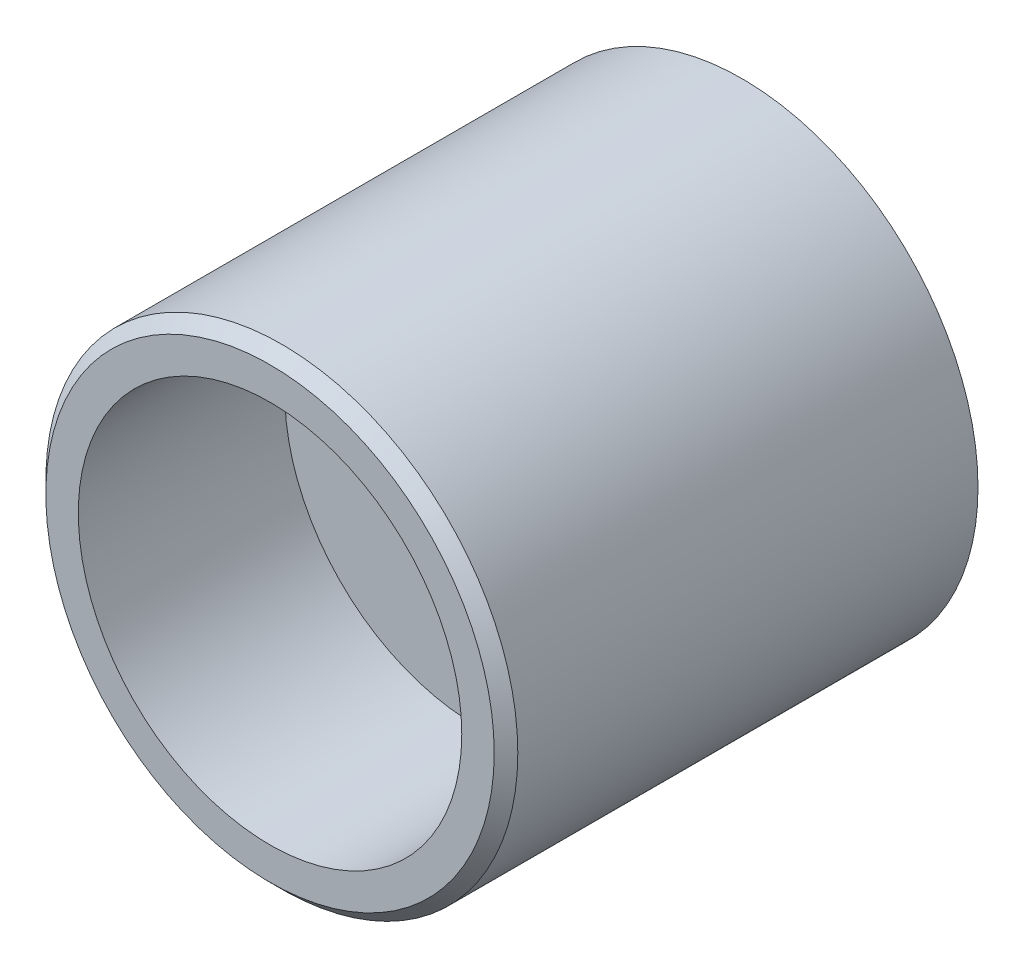
SolidWorks part; units mm, degrees
material "POM copolymère d'acétal"
ref_plane "Face" through (0, 0, 0) normal (0, 0, 1) x (1, 0, 0)
ref_plane "Dessus" through (0, 0, 0) normal (0, 1, 0) x (1, 0, 0)
ref_plane "Droite" through (0, 0, 0) normal (1, 0, 0) x (0, 0, -1)
sketch "Esquisse1" plane through (0, 0, 0) normal (0, 0, 1) x (1, 0, 0)
  circle A0 centre (0, 0) radius 4
extrude "Boss.-Extru.1" add sketch "Esquisse1" along normal blind 8
hole_wizard "Chambrage pour vis à tête hexagonale M31" positions "Esquisse3" profile "Esquisse2" counterbore size "M3" standard "Iso" end condition through all
sketch "Esquisse3" plane through (0, 0, 8) normal (0, 0, 1) x (1, 0, 0)
  point P0 (0, 0)
sketch "Esquisse2" plane through (0, 0, 8) normal (1, 0, 0) x (0, -1, 0)
  line L0 (0, 0) -> (0, 8)
  line L1 (0, 8) -> (1.7, 8)
  line L3 (1.7, 8) -> (1.7, 3.5)
  line L4 (1.7, 3.5) -> (3.25, 3.5)
  line L5 (3.25, 3.5) -> (3.25, 0)
  line L7 (3.25, 0) -> (0, 0)
  line L11 (0, -6.35) -> (0, 107.95) construction
  dimension "Diamètre du perçage jusqu'au prochain" = 3.4
  dimension "Profondeur du perçage jusqu'au prochain" = 8
  dimension "Diamètre du chambrage" = 6.5
  dimension "Profondeur du chambrage" = 3.5
chamfer "Chanfrein1" distance 0.2 angle 45 1 edges at (4, 0, 8)
